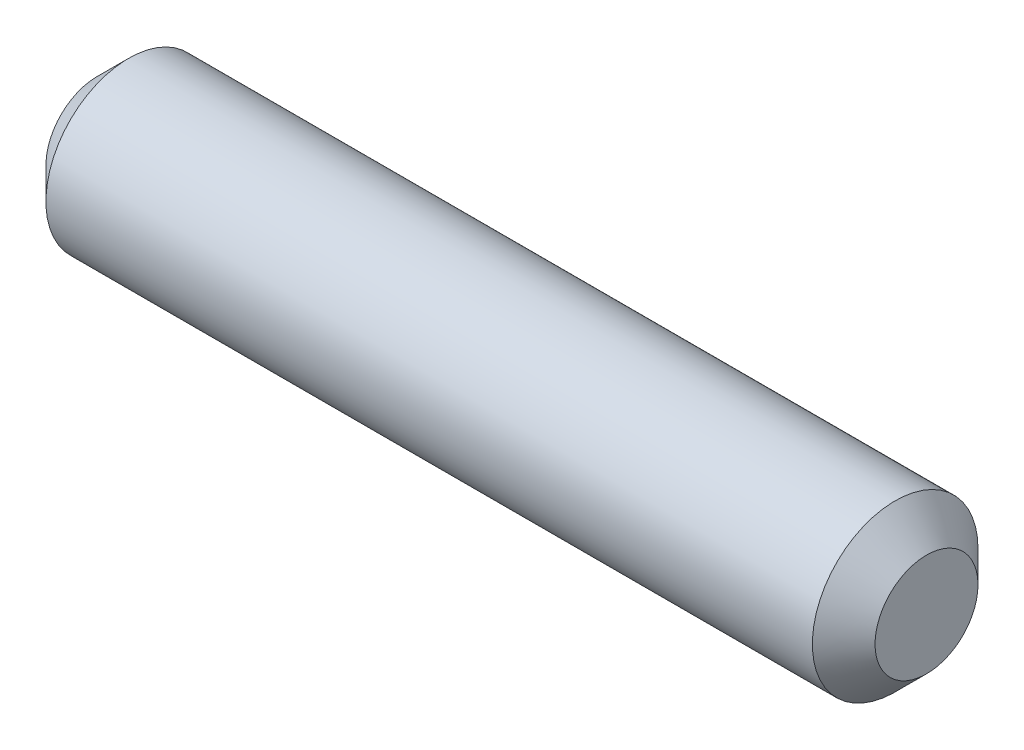
SolidWorks part; units mm, degrees
ref_plane "Front Plane" through (0, 0, 0) normal (0, 0, 1) x (1, 0, 0)
ref_plane "Top Plane" through (0, 0, 0) normal (0, 1, 0) x (1, 0, 0)
ref_plane "Right Plane" through (0, 0, 0) normal (1, 0, 0) x (0, 0, -1)
sketch "Sketch1" plane through (0, 0, 0) normal (1, 0, 0) x (0, 0, -1)
  circle A0 centre (0, 0) radius 1.585
  dimension "D1" = 3.17
extrude "Boss-Extrude1" add sketch "Sketch1" along normal mid plane 15.87
chamfer "Chamfer1" distance 0.6 angle 45 2 edges at (7.935, 0, -1.585) (-7.935, 0, -1.585)
